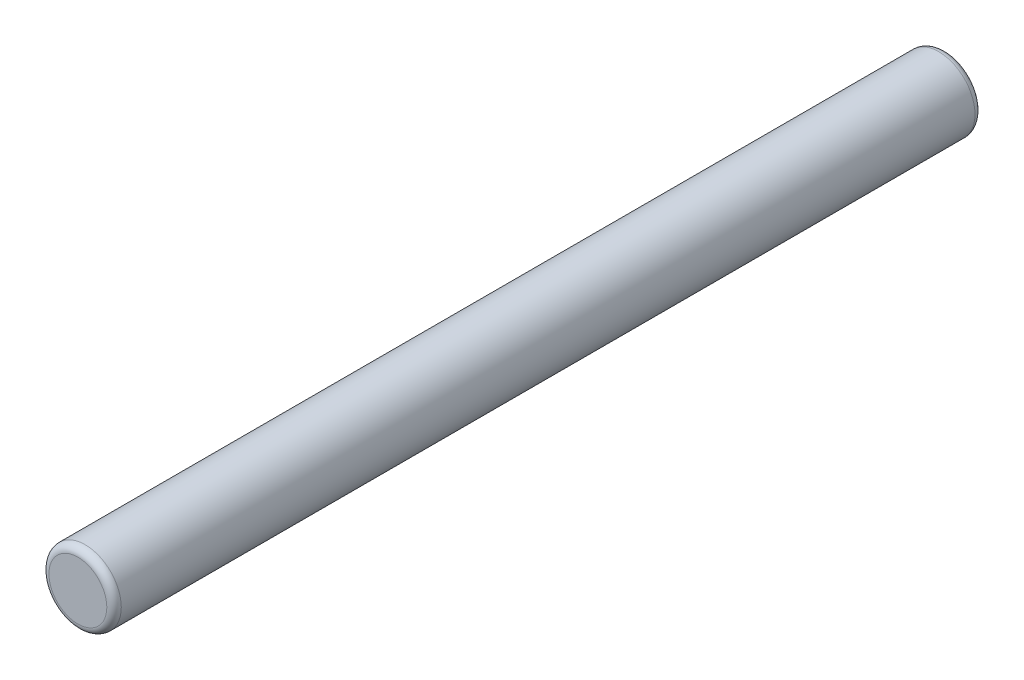
SolidWorks part; units mm, degrees
material "AISI 316 Annealed Stainless Steel Bar (SS)"
ref_plane "Front Plane" through (0, 0, 0) normal (0, 0, 1) x (1, 0, 0)
ref_plane "Top Plane" through (0, 0, 0) normal (0, 1, 0) x (1, 0, 0)
ref_plane "Right Plane" through (0, 0, 0) normal (1, 0, 0) x (0, 0, -1)
sketch "Sketch1" plane through (0, 0, 0) normal (0, 0, 1) x (1, 0, 0)
  circle A0 centre (0, 0) radius 2.5
  dimension "D1" = 5
extrude "Boss-Extrude1" add sketch "Sketch1" along normal blind 60
fillet "Fillet1" radius 0.5 2 edges at (2.5, 0, 0) (2.5, 0, 60)
